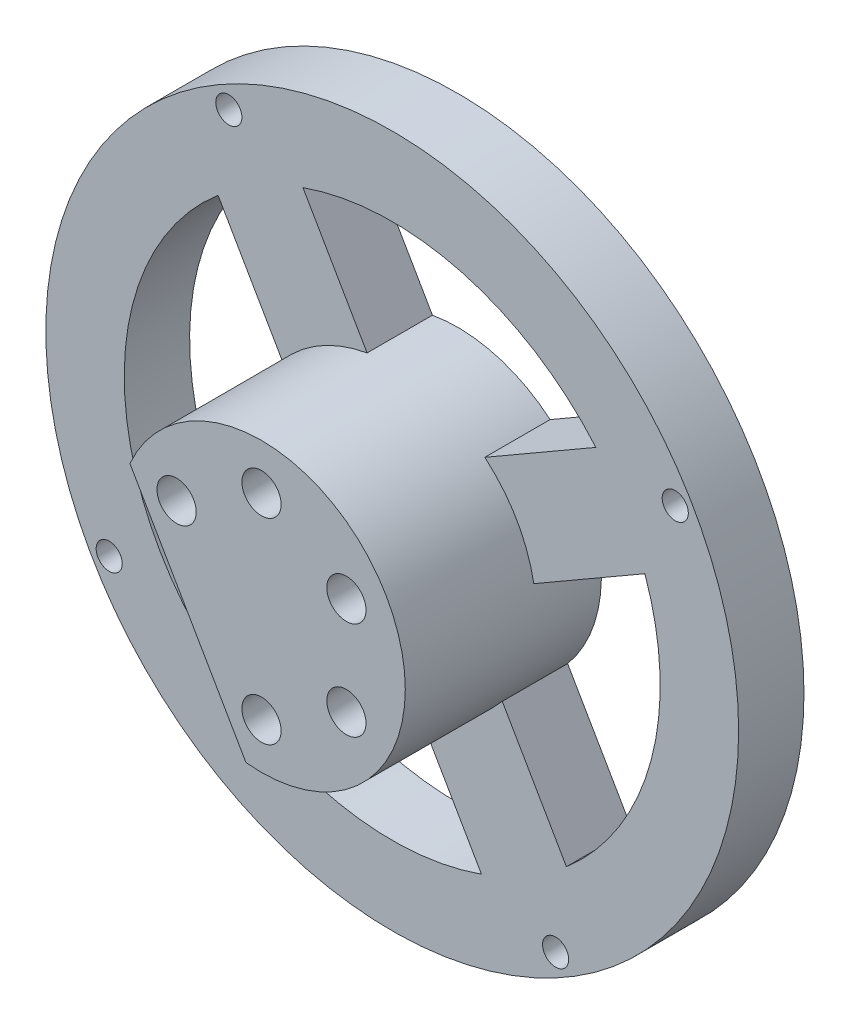
SolidWorks part; units mm, degrees
ref_plane "Plan de face" through (0, 0, 0) normal (0, 0, 1) x (1, 0, 0)
ref_plane "Plan de dessus" through (0, 0, 0) normal (0, 1, 0) x (1, 0, 0)
ref_plane "Plan de droite" through (0, 0, 0) normal (1, 0, 0) x (0, 0, -1)
sketch "Esquisse1"
sketch_block_instance "Bloc1-1"
sketch_block "Bloc1" parameters "D1"=2
sketch "Esquisse2" plane through (0, 0, 0) normal (0, 0, 1) x (1, 0, 0)
  line L1 (0, 15) -> (0, -15) construction
  line L2 (0, 0) -> (-17.5, 30.3109) construction
  line L3 (-26.6493, 31.1579) -> (-16.8362, 14.1612)
  line L4 (-13.6589, 38.6579) -> (-3.8459, 21.6612)
  line L5 (38.6579, 13.6589) -> (21.6612, 3.8459)
  line L6 (31.1579, 26.6493) -> (14.1612, 16.8362)
  line L7 (13.6589, -38.6579) -> (3.8459, -21.6612)
  line L8 (26.6493, -31.1579) -> (16.8362, -14.1612)
  line L9 (-38.6579, -13.6589) -> (-21.6612, -3.8459)
  line L10 (-31.1579, -26.6493) -> (-14.1612, -16.8362)
  circle A0 centre (0, -15) radius 3
  circle A1 centre (0, -15) radius 3 construction
  circle A2 centre (12.9904, -7.5) radius 3
  circle A3 centre (12.9904, 7.5) radius 3
  circle A4 centre (0, 15) radius 3
  circle A5 centre (-12.9904, 7.5) radius 3
  arc A6 (-3.8459, 21.6612) -> (14.1612, 16.8362) centre (0, 0) cw
  arc A7 (-13.6589, 38.6579) -> (31.1579, 26.6493) centre (0, 0) cw
  arc A8 (21.6612, 3.8459) -> (16.8362, -14.1612) centre (0, 0) cw
  arc A9 (38.6579, 13.6589) -> (26.6493, -31.1579) centre (0, 0) cw
  arc A10 (3.8459, -21.6612) -> (-14.1612, -16.8362) centre (0, 0) cw
  arc A11 (13.6589, -38.6579) -> (-31.1579, -26.6493) centre (0, 0) cw
  arc A12 (-21.6612, -3.8459) -> (-16.8362, 14.1612) centre (0, 0) cw
  arc A13 (-38.6579, -13.6589) -> (-26.6493, 31.1579) centre (0, 0) cw
  circle A14 centre (0, 0) radius 53
  point P15 (0, 0)
  point P32 (0, 0)
  point P36 (-21.6612, -3.8459)
  point P37 (-38.6579, -13.6589)
  point P50 (0, 0)
  dimension "D1" = 3
  dimension "D2" = 106
  dimension "D4" = 12
  dimension "D5" = 22
  dimension "D6" = 15
  dimension "D3" = 4
extrude "Boss.-Extru.1" add sketch "Esquisse2" along normal blind 10
sketch "Esquisse3" plane through (0, 0, 10) normal (0, 0, 1) x (1, 0, 0)
  circle A0 centre (0, 0) radius 22
  circle A1 centre (-12.9904, 7.5) radius 3
  circle A2 centre (-12.9904, 7.5) radius 3 construction
  circle A3 centre (0, 15) radius 3
  circle A4 centre (12.9904, 7.5) radius 3
  circle A5 centre (12.9904, -7.5) radius 3
  circle A6 centre (0, -15) radius 3
  point P9 (12.9904, -7.5)
  point P10 (12.9904, 7.5)
  point P19 (0, 0)
  dimension "D1" = 5
extrude "Boss.-Extru.2" add sketch "Esquisse3" along normal blind 20
sketch "Esquisse4" plane through (0, 0, 0) normal (0, 0, -1) x (-1, 0, 0)
  line L0 (12.9904, 7.5) -> (0, 0) construction
  line L1 (15.8771, 2.5) -> (18.7639, 7.5)
  line L2 (18.7639, 7.5) -> (15.8771, 12.5)
  line L3 (15.8771, 12.5) -> (10.1036, 12.5)
  line L4 (10.1036, 12.5) -> (7.2169, 7.5)
  line L5 (7.2169, 7.5) -> (10.1036, 2.5)
  line L6 (10.1036, 2.5) -> (15.8771, 2.5)
  line L7 (-2.8868, 20) -> (-5.7735, 15)
  line L8 (-5.7735, 15) -> (-2.8868, 10)
  line L9 (-2.8868, 10) -> (2.8868, 10)
  line L10 (2.8868, 10) -> (5.7735, 15)
  line L11 (5.7735, 15) -> (2.8868, 20)
  line L12 (2.8868, 20) -> (-2.8868, 20)
  line L13 (-18.7639, 7.5) -> (-15.8771, 2.5)
  line L14 (-15.8771, 2.5) -> (-10.1036, 2.5)
  line L15 (-10.1036, 2.5) -> (-7.2169, 7.5)
  line L16 (-7.2169, 7.5) -> (-10.1036, 12.5)
  line L17 (-10.1036, 12.5) -> (-15.8771, 12.5)
  line L18 (-15.8771, 12.5) -> (-18.7639, 7.5)
  line L19 (-15.8771, -12.5) -> (-10.1036, -12.5)
  line L20 (-10.1036, -12.5) -> (-7.2169, -7.5)
  line L21 (-7.2169, -7.5) -> (-10.1036, -2.5)
  line L22 (-10.1036, -2.5) -> (-15.8771, -2.5)
  line L23 (-15.8771, -2.5) -> (-18.7639, -7.5)
  line L24 (-18.7639, -7.5) -> (-15.8771, -12.5)
  line L25 (2.8868, -20) -> (5.7735, -15)
  line L26 (5.7735, -15) -> (2.8868, -10)
  line L27 (2.8868, -10) -> (-2.8868, -10)
  line L28 (-2.8868, -10) -> (-5.7735, -15)
  line L29 (-5.7735, -15) -> (-2.8868, -20)
  line L30 (-2.8868, -20) -> (2.8868, -20)
  circle A0 centre (12.9904, 7.5) radius 5 construction
  point P37 (0, 0)
  dimension "D1" = 10
extrude "Enlèv. mat.-Extru.1" cut sketch "Esquisse4" against normal blind 6
sketch "Esquisse5" plane through (0, 0, 0) normal (0, 0, -1) x (-1, 0, 0)
  line L0 (2.3842, -21.8704) -> (20.1324, 8.8704)
  line L1 (20.1324, 8.8704) -> (38.6579, -13.6589)
  line L2 (2.3842, -21.8704) -> (31.1579, -26.6493)
  line L3 (14.1612, -16.8362) -> (31.1579, -26.6493) construction
  line L4 (16.8362, 14.1612) -> (26.6493, 31.1579) construction
  arc A0 (-3.8459, -21.6612) -> (14.1612, -16.8362) centre (0, 0) ccw construction
  arc A1 (21.6612, -3.8459) -> (16.8362, 14.1612) centre (0, 0) ccw construction
  arc A2 (-13.6589, -38.6579) -> (31.1579, -26.6493) centre (0, 0) ccw construction
  arc A3 (38.6579, -13.6589) -> (31.1579, -26.6493) centre (0, 0) cw
  dimension "D1" = 13
extrude "Enlèv. mat.-Extru.2" cut sketch "Esquisse5" against normal through all
sketch "Esquisse7" plane through (0, 0, 0) normal (0, 0, -1) x (-1, 0, 0)
  line L0 (0, 0) -> (-45.8993, 26.5) construction
  line L2 (-15.8771, 12.5) -> (-18.7639, 7.5) construction
  circle A0 centre (0, 0) radius 53 construction
  circle A1 centre (-43.3013, 25) radius 2
  circle A2 centre (25, 43.3013) radius 2
  circle A3 centre (43.3013, -25) radius 2
  circle A4 centre (-25, -43.3013) radius 2
  point P9 (28.667, 43.7114)
  point P10 (0, 0)
  point P18 (0, 0)
  dimension "D1" = 4
  dimension "D2" = 50
extrude "Enlèv. mat.-Extru.3" cut sketch "Esquisse7" against normal through all
